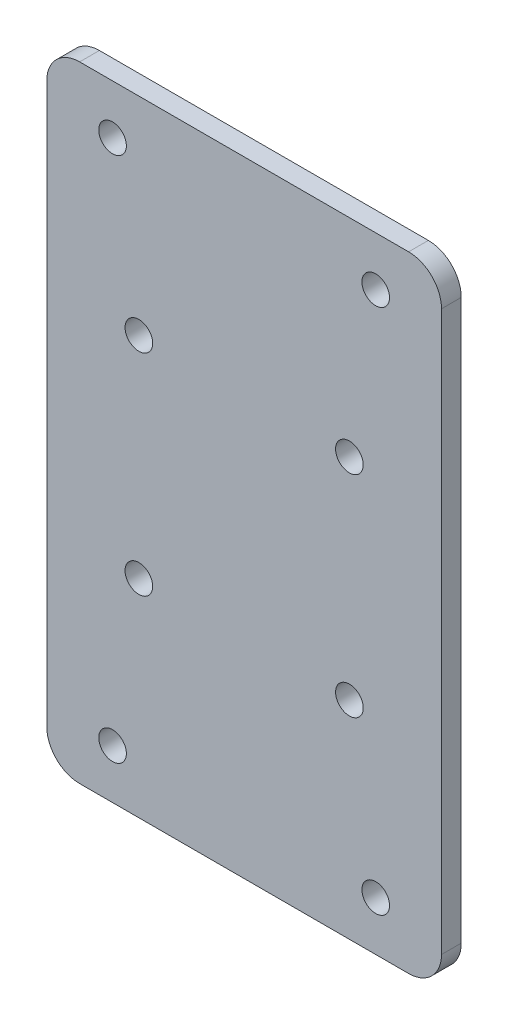
SolidWorks part; units mm, degrees
ref_plane "正面" through (0, 0, 0) normal (0, 0, 1) x (1, 0, 0)
ref_plane "平面" through (0, 0, 0) normal (0, 1, 0) x (1, 0, 0)
ref_plane "右側面" through (0, 0, 0) normal (1, 0, 0) x (0, 0, -1)
sketch "ｽｹｯﾁ1" plane through (0, 0, 0) normal (0, 0, 1) x (1, 0, 0)
  line L1 (-30, 47.5) -> (30, 47.5)
  line L2 (-30, 47.5) -> (-30, -47.5)
  line L3 (-30, -47.5) -> (30, -47.5)
  line L4 (30, 47.5) -> (30, -47.5)
  line L5 (-30, 47.5) -> (30, -47.5) construction
  line L6 (-30, -47.5) -> (30, 47.5) construction
  line L7 (-16, 16) -> (16, 16) construction
  line L8 (-16, 16) -> (-16, -16) construction
  line L9 (-16, -16) -> (16, -16) construction
  line L10 (16, 16) -> (16, -16) construction
  line L11 (-16, 16) -> (16, -16) construction
  line L12 (-16, -16) -> (16, 16) construction
  line L13 (-20, -40) -> (20, -40) construction
  line L14 (-20, -40) -> (-20, 40) construction
  line L15 (-20, 40) -> (20, 40) construction
  line L16 (20, -40) -> (20, 40) construction
  line L17 (-20, -40) -> (20, 40) construction
  line L18 (-20, 40) -> (20, -40) construction
  circle A0 centre (-16, 16) radius 2.1
  circle A1 centre (16, 16) radius 2.1
  circle A2 centre (-16, -16) radius 2.1
  circle A3 centre (16, -16) radius 2.1
  circle A4 centre (-20, 40) radius 2.1
  circle A5 centre (-20, -40) radius 2.1
  circle A6 centre (20, 40) radius 2.1
  circle A7 centre (20, -40) radius 2.1
  point P0 (0, 0)
  point P5 (0, 0)
  point P18 (0, 0)
  dimension "D1" = 4.2
  dimension "D4" = 10
  dimension "D2" = 32
  dimension "D3" = 32
  dimension "D5" = 7.5
  dimension "D6" = 40
  dimension "D7" = 80
extrude "ﾎﾞｽ - 押し出し1" add sketch "ｽｹｯﾁ1" along normal blind 3
fillet "ﾌｨﾚｯﾄ1" radius 5 4 edges at (-30, -47.5, 1.5) (30, -47.5, 1.5) (-30, 47.5, 1.5) (30, 47.5, 1.5)
